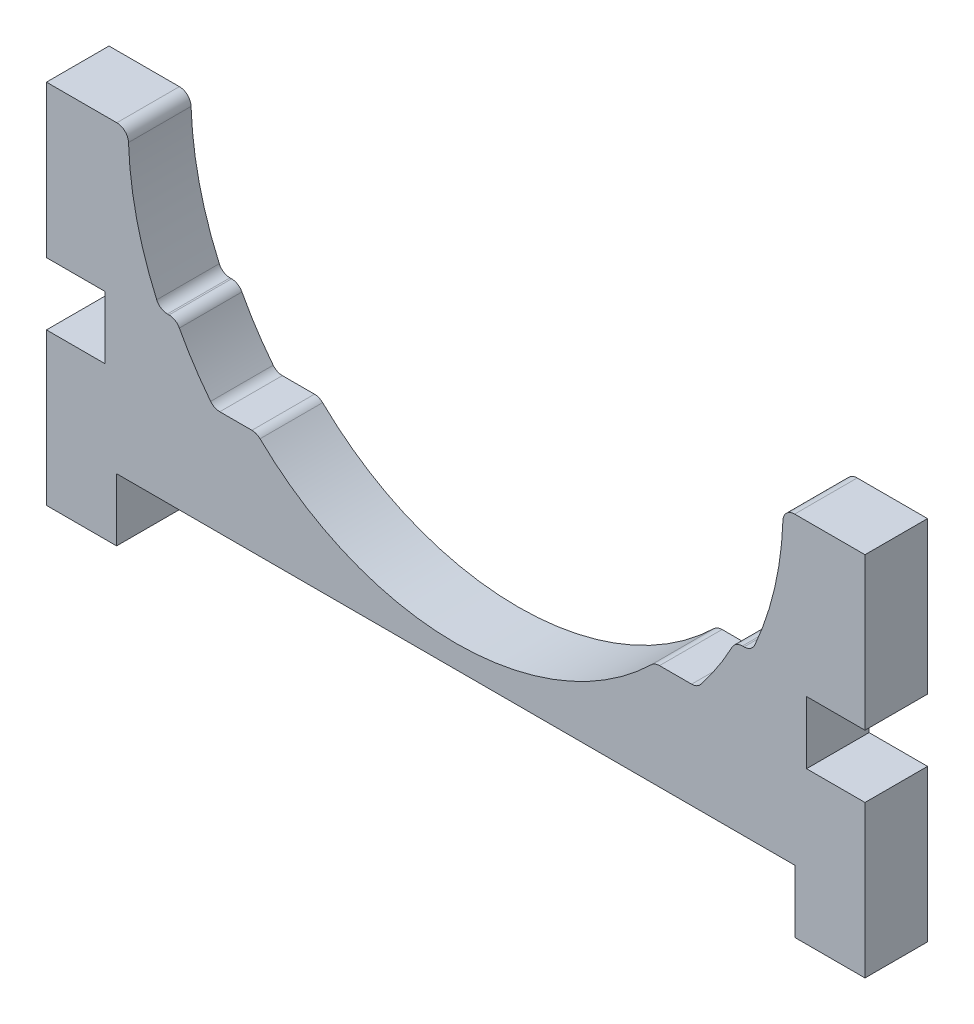
SolidWorks part; units mm, degrees
ref_plane "Front Plane" through (0, 0, 0) normal (0, 0, 1) x (1, 0, 0)
ref_plane "Top Plane" through (0, 0, 0) normal (0, 1, 0) x (1, 0, 0)
ref_plane "Right Plane" through (0, 0, 0) normal (1, 0, 0) x (0, 0, -1)
sketch "Model" plane through (0, 0, 0) normal (0, 0, 1) x (1, 0, 0)
  line L0 (10.3423, 19.35) -> (10.4834, 19.35)
  line L1 (14.8242, 14.35) -> (17.5715, 14.35)
  line L2 (63.9828, 31.35) -> (70, 31.35)
  line L3 (70, 31.35) -> (70, 18.35)
  line L4 (70, 18.35) -> (65, 18.35)
  line L5 (65, 18.35) -> (65, 13)
  line L6 (65, 13) -> (70, 13)
  line L7 (70, 13) -> (70, 0)
  line L8 (70, 0) -> (64, 0)
  line L9 (64, 0) -> (64, 5.35)
  line L10 (55.1758, 14.35) -> (52.4285, 14.35)
  line L11 (59.6577, 19.35) -> (59.5166, 19.35)
  line L12 (6, 5.35) -> (64, 5.35)
  line L13 (6, 0) -> (6, 5.35)
  line L14 (0, 0) -> (6, 0)
  line L15 (0, 13) -> (0, 0)
  line L16 (5, 13) -> (0, 13)
  line L17 (5, 18.35) -> (5, 13)
  line L18 (0, 18.35) -> (5, 18.35)
  line L19 (0, 31.35) -> (0, 18.35)
  line L20 (6.0172, 31.35) -> (0, 31.35)
  line L21 (35, 31.35) -> (35, -6.9894) construction
  arc A0 (7.0167, 30.3845) -> (6.0172, 31.35) centre (6.0172, 30.35) ccw
  arc A1 (7.0167, 30.3845) -> (9.4291, 19.9426) centre (35, 31.35) ccw
  arc A2 (9.4291, 19.9426) -> (10.3423, 19.35) centre (10.3423, 20.35) ccw
  arc A3 (11.3669, 18.8185) -> (10.4834, 19.35) centre (10.4834, 18.35) ccw
  arc A4 (11.3669, 18.8185) -> (14.0407, 14.7286) centre (35, 31.35) ccw
  arc A5 (14.0407, 14.7286) -> (14.8242, 14.35) centre (14.8242, 15.35) ccw
  arc A6 (18.2671, 14.0684) -> (17.5715, 14.35) centre (17.5715, 13.35) ccw
  arc A7 (51.7329, 14.0684) -> (52.4285, 14.35) centre (52.4285, 13.35) cw
  arc A8 (55.9593, 14.7286) -> (55.1758, 14.35) centre (55.1758, 15.35) cw
  arc A9 (58.6331, 18.8185) -> (55.9593, 14.7286) centre (35, 31.35) cw
  arc A10 (58.6331, 18.8185) -> (59.5166, 19.35) centre (59.5166, 18.35) cw
  arc A11 (60.5709, 19.9426) -> (59.6577, 19.35) centre (59.6577, 20.35) cw
  arc A12 (62.9833, 30.3845) -> (60.5709, 19.9426) centre (35, 31.35) cw
  arc A13 (62.9833, 30.3845) -> (63.9828, 31.35) centre (63.9828, 30.35) cw
  arc A14 (18.2671, 14.0684) -> (51.7329, 14.0684) centre (35, 31.35) ccw
  point P47 (35, 5.35)
  dimension "D8" = 24.055
  dimension "D9" = 1
  dimension "D10" = 1
  dimension "D11" = 1
  dimension "D12" = 1
  dimension "D13" = 1
  dimension "D25" = 1.945
  dimension "D2" = 5.35
  dimension "D3" = 6
  dimension "D4" = 5.35
  dimension "D5" = 5
  dimension "D6" = 13
  dimension "D7" = 31.35
  dimension "D14" = 6.0172
  dimension "D15" = 6.0172
  dimension "D16" = 10.3423
  dimension "D17" = 10.4834
  dimension "D18" = 14.8242
  dimension "D19" = 17.5715
  dimension "D20" = 16
  dimension "D21" = 18
  dimension "D22" = 11
  dimension "D23" = 1
  dimension "D24" = 13
extrude "Boss-Extrude1" add sketch "Model" along normal blind 5.35
